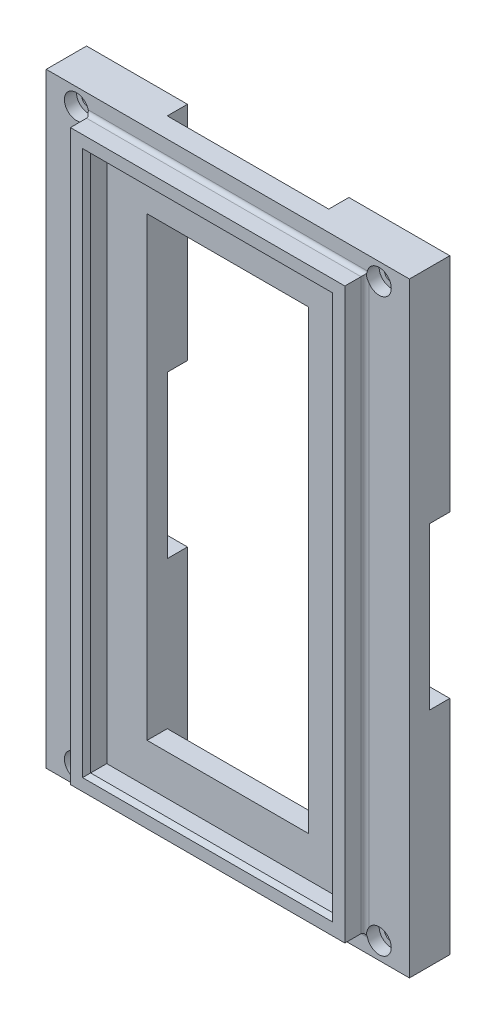
SolidWorks part; units mm, degrees
material "Custom Plastic"
ref_plane "Front Plane" through (0, 0, 0) normal (0, 0, 1) x (1, 0, 0)
ref_plane "Top Plane" through (0, 0, 0) normal (0, 1, 0) x (1, 0, 0)
ref_plane "Right Plane" through (0, 0, 0) normal (1, 0, 0) x (0, 0, -1)
sketch "Sketch1" plane through (0, 0, 0) normal (0, 0, 1) x (1, 0, 0)
  line L1 (107.4, 77.4) -> (197.4, 77.4)
  line L2 (107.4, 77.4) -> (107.4, 227.4)
  line L3 (107.4, 227.4) -> (197.4, 227.4)
  line L4 (0, 304.8) -> (0, 0)
  line L5 (0, 0) -> (304.8, 0)
  line L6 (304.8, 0) -> (304.8, 304.8)
  line L7 (304.8, 304.8) -> (0, 304.8)
  line L8 (0, 304.8) -> (0, 0)
  line L9 (0, 0) -> (304.8, 0)
  line L10 (304.8, 0) -> (304.8, 304.8)
  line L11 (304.8, 304.8) -> (0, 304.8)
  line L12 (197.4, 77.4) -> (197.4, 227.4)
  line L13 (107.4, 77.4) -> (197.4, 227.4) construction
  line L14 (107.4, 227.4) -> (197.4, 77.4) construction
  circle A0 centre (152.4, 152.4) radius 12.5 construction
  dimension "D1" = 0
extrude "Boss-Extrude1" add sketch "Sketch1" along normal blind 10 contours L2 L1 L12 L3
sketch "Sketch2" plane through (0, 0, 0) normal (0, 0, -1) x (-1, 0, 0)
  line L0 (-142.4, 60.3139) -> (-132.4, 60.3139)
  line L1 (-162.4, 60.3139) -> (-172.4, 60.3139)
  line L5 (-287.9686, 162.4) -> (-287.9686, 142.4)
  line L6 (-142.4, 142.4) -> (0, 142.4)
  line L8 (-142.4, 162.4) -> (0, 162.4)
  line L9 (0, 142.4) -> (0, 162.4)
  line L10 (-162.4, 142.4) -> (-162.4, 60.3139)
  line L13 (-162.4, 60.3139) -> (-142.4, 60.3139)
  line L14 (-142.4, 142.4) -> (-142.4, 60.3139)
  line L17 (-162.4, 244.2764) -> (-142.4, 244.2764)
  line L18 (-142.4, 162.4) -> (-142.4, 244.2764)
  line L19 (-162.4, 142.4) -> (-287.9686, 142.4)
  line L20 (-162.4, 162.4) -> (-162.4, 244.2764)
  line L21 (-162.4, 162.4) -> (-287.9686, 162.4)
  line L22 (0, 142.4) -> (0, 132.4)
  line L23 (-132.4, 60.3139) -> (-172.4, 60.3139)
  line L24 (-132.4, 60.3139) -> (-132.4, 244.2764)
  line L25 (-132.4, 244.2764) -> (-172.4, 244.2764)
  line L26 (-172.4, 60.3139) -> (-172.4, 244.2764)
  line L27 (0, 162.4) -> (0, 172.4)
  line L29 (0, 172.4) -> (-287.9686, 172.4)
  line L30 (0, 172.4) -> (0, 132.4)
  line L31 (0, 132.4) -> (-287.9686, 132.4)
  line L32 (-287.9686, 172.4) -> (-287.9686, 132.4)
extrude "Cut-Extrude2" cut sketch "Sketch2" against normal blind 5 contours L6 L9 L8 L18 L17 L20 L21 L5 L19 L10 L13 L14 | L24 L23 L26 L25 | L30 L29 L32 L31
sketch "Sketch3" plane through (0, 0, 10) normal (0, 0, 1) x (1, 0, 0)
  line L0 (122.4, 85.9) -> (107.4, 85.9) construction
  line L1 (114.9, 85.9) -> (114.9, 77.4) construction
  line L3 (182.4, 85.9) -> (197.4, 85.9) construction
  line L8 (122.4, 85.9) -> (182.4, 85.9)
  line L9 (182.4, 85.9) -> (182.4, 218.9)
  line L10 (182.4, 218.9) -> (122.4, 218.9)
  line L11 (122.4, 218.9) -> (122.4, 85.9)
  line L12 (197.4, 227.4) -> (107.4, 227.4)
  line L13 (107.4, 227.4) -> (107.4, 77.4)
  line L14 (107.4, 77.4) -> (197.4, 77.4)
  line L15 (197.4, 77.4) -> (197.4, 227.4)
  line L16 (197.4, 227.4) -> (107.4, 227.4)
  line L17 (107.4, 227.4) -> (107.4, 77.4)
  line L18 (107.4, 77.4) -> (197.4, 77.4)
  line L19 (197.4, 77.4) -> (197.4, 227.4)
  line L20 (189.9, 85.9) -> (189.9, 77.4) construction
  line L21 (122.4, 218.9) -> (107.4, 218.9) construction
  line L22 (114.9, 218.9) -> (114.9, 227.4) construction
  line L23 (182.4, 218.9) -> (197.4, 218.9) construction
  line L24 (189.9, 218.9) -> (189.9, 227.4) construction
  circle A0 centre (114.9, 81.65) radius 1.7
  circle A1 centre (189.9, 81.65) radius 1.7
  circle A2 centre (114.9, 223.15) radius 1.7
  circle A3 centre (189.9, 223.15) radius 1.7
  dimension "D2" = 0
extrude "Cut-Extrude3" cut sketch "Sketch3" against normal blind 12 contours A1 | A3 | A2 | A0
sketch "Sketch4" plane through (0, 0, 10) normal (0, 0, 1) x (1, 0, 0)
  line L4 (122.4, 85.9) -> (182.4, 85.9)
  line L5 (182.4, 85.9) -> (182.4, 218.9)
  line L6 (182.4, 218.9) -> (122.4, 218.9)
  line L7 (122.4, 218.9) -> (122.4, 85.9)
  line L8 (122.4, 85.9) -> (182.4, 85.9)
  line L9 (182.4, 85.9) -> (182.4, 218.9)
  line L10 (182.4, 218.9) -> (122.4, 218.9)
  line L11 (122.4, 218.9) -> (122.4, 85.9)
  line L20 (118.4, 81.9) -> (186.4, 81.9)
  line L21 (186.4, 81.9) -> (186.4, 222.9)
  line L22 (186.4, 222.9) -> (118.4, 222.9)
  line L23 (118.4, 222.9) -> (118.4, 81.9)
  line L24 (118.4, 81.9) -> (186.4, 81.9)
  line L25 (186.4, 81.9) -> (186.4, 222.9)
  line L26 (186.4, 222.9) -> (118.4, 222.9)
  line L27 (118.4, 222.9) -> (118.4, 81.9)
  dimension "D1" = 0
  dimension "D2" = 4
extrude "Boss-Extrude2" add sketch "Sketch4" along normal blind 5
fillet "Fillet1" radius 1 4 edges at (186.4, 152.4, 10) (152.4, 81.9, 10) (152.4, 222.9, 10) (118.4, 152.4, 10)
chamfer "Chamfer1" distance 1 angle 45 4 edges at (152.4, 218.9, 15) (182.4, 152.4, 15) (152.4, 85.9, 15) (122.4, 152.4, 15)
sketch "Sketch5" plane through (0, 0, 10) normal (0, 0, 1) x (1, 0, 0)
  line L12 (187.4, 217.4) -> (117.4, 217.4)
  line L14 (117.4, 217.4) -> (117.4, 87.4)
  line L20 (117.4, 87.4) -> (187.4, 87.4)
  line L21 (117.4, 87.4) -> (187.4, 87.4)
  line L22 (187.4, 87.4) -> (187.4, 217.4)
  line L23 (187.4, 87.4) -> (187.4, 217.4)
  line L26 (132.4, 95.9) -> (172.4, 95.9)
  line L27 (172.4, 95.9) -> (172.4, 208.9)
  line L28 (172.4, 208.9) -> (132.4, 208.9)
  line L29 (132.4, 208.9) -> (132.4, 95.9)
  line L30 (132.4, 95.9) -> (172.4, 95.9)
  line L31 (172.4, 95.9) -> (172.4, 208.9)
  line L32 (172.4, 208.9) -> (132.4, 208.9)
  line L33 (132.4, 208.9) -> (132.4, 95.9)
  dimension "D1" = 10
  dimension "D2" = 10
extrude "Cut-Extrude4" cut sketch "Sketch5" against normal blind 10
sketch "Sketch6" plane through (0, 0, 10) normal (0, 0, 1) x (1, 0, 0)
  circle A0 centre (189.9, 223.15) radius 1.7 construction
  circle A1 centre (189.9, 81.65) radius 1.7 construction
  circle A2 centre (114.9, 81.65) radius 1.7 construction
  circle A3 centre (114.9, 223.15) radius 1.7 construction
  circle A4 centre (189.9, 223.15) radius 1.7
  circle A5 centre (189.9, 81.65) radius 1.7
  circle A6 centre (114.9, 81.65) radius 1.7
  circle A7 centre (114.9, 223.15) radius 1.7
  circle A8 centre (114.9, 223.15) radius 3
  circle A9 centre (114.9, 81.65) radius 3
  circle A10 centre (189.9, 81.65) radius 3
  circle A11 centre (189.9, 223.15) radius 3
extrude "Cut-Extrude5" cut sketch "Sketch6" against normal mid plane 6
